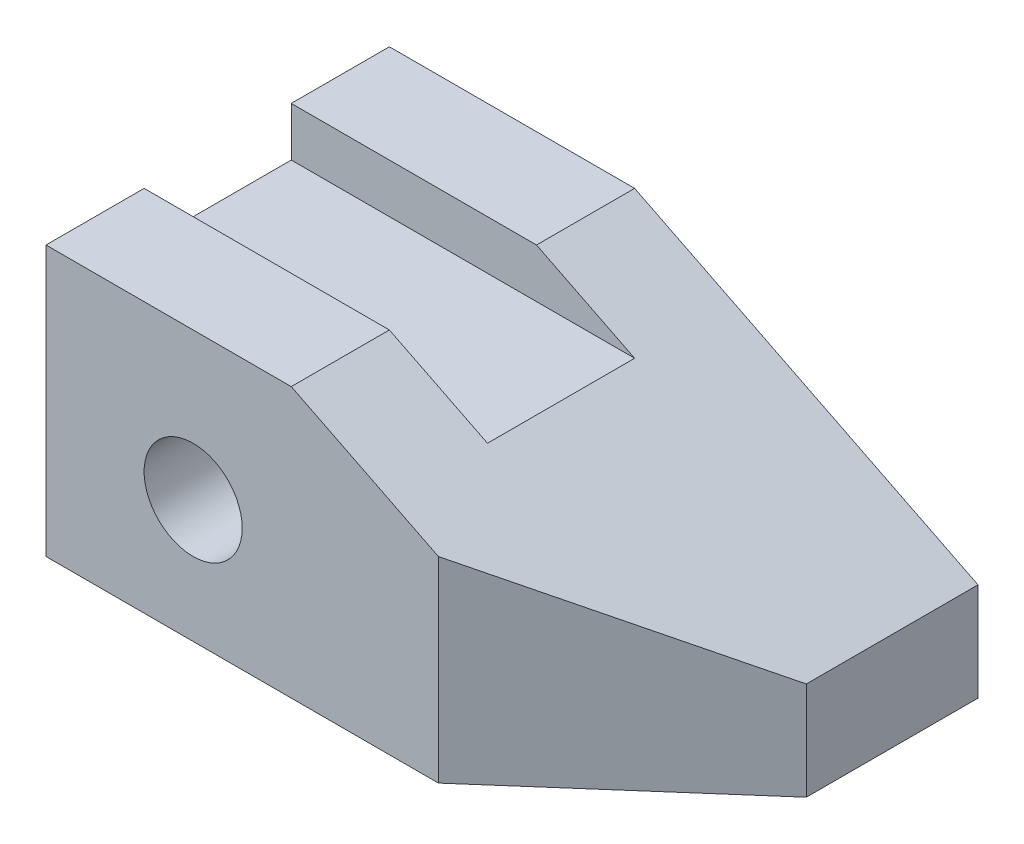
SolidWorks part; units mm, degrees
ref_plane "Front Plane" through (0, 0, 0) normal (0, 0, 1) x (1, 0, 0)
ref_plane "Top Plane" through (0, 0, 0) normal (0, 1, 0) x (1, 0, 0)
ref_plane "Right Plane" through (0, 0, 0) normal (1, 0, 0) x (0, 0, -1)
sketch "Sketch2" plane through (0, 0, 0) normal (0, 1, 0) x (1, 0, 0)
  line L1 (0, 0) -> (152.4, 0)
  line L2 (0, 0) -> (0, 88.9)
  line L3 (0, 88.9) -> (152.4, 88.9)
  line L4 (152.4, 0) -> (152.4, 88.9)
  dimension "D1" = 152.4
  dimension "D2" = 88.9
extrude "Boss-Extrude1" add sketch "Sketch2" along normal blind 69.85
sketch "Sketch3" plane through (0, 0, 0) normal (0, 0, 1) x (1, 0, 0)
  line L0 (63.5, 69.85) -> (152.4, 25.4)
  line L1 (0, 69.85) -> (152.4, 69.85) construction
  line L2 (152.4, 69.85) -> (152.4, 0) construction
  line L3 (0, 69.85) -> (0, 0) construction
  line L4 (0, 0) -> (152.4, 0) construction
  circle A0 centre (38.1, 31.75) radius 12.7
  line M2 (152.4, 0) -> (152.4, 69.85)
  line M3 (152.4, 69.85) -> (0, 69.85)
  dimension "D3" = 25.4
  dimension "D1" = 63.5
  dimension "D2" = 25.4
  dimension "D4" = 38.1
  dimension "D5" = 31.75
extrude "Cut-Extrude1" cut sketch "Sketch3" against normal through all contours L0 M3 M2 | A0
sketch "Sketch5" plane through (0, 69.85, 0) normal (0, 1, 0) x (1, 0, 0)
  line L0 (101.6, 0) -> (152.4, 44.45)
  line L1 (63.5, 88.9) -> (152.4, 88.9) construction
  line L2 (152.4, 88.9) -> (152.4, 0) construction
  line L3 (63.5, 0) -> (152.4, 0) construction
  line L4 (0, 88.9) -> (0, 0) construction
  line L6 (152.4, 0) -> (101.6, 0)
  line L7 (152.4, 0) -> (152.4, 44.45)
  dimension "D1" = 44.45
  dimension "D2" = 101.6
extrude "Cut-Extrude4" cut sketch "Sketch5" against normal through all
sketch "Sketch6" plane through (0, 0, 0) normal (-1, 0, 0) x (0, 0, 1)
  line L0 (-88.9, 69.85) -> (0, 69.85) construction
  line L1 (-63.5, 69.85) -> (-25.4, 69.85)
  line L2 (-63.5, 69.85) -> (-63.5, 57.15)
  line L3 (-63.5, 57.15) -> (-25.4, 57.15)
  line L4 (-25.4, 69.85) -> (-25.4, 57.15)
  line L5 (-88.9, 69.85) -> (-88.9, 0) construction
  dimension "D1" = 12.7
  dimension "D2" = 38.1
  dimension "D3" = 25.4
extrude "Cut-Extrude5" cut sketch "Sketch6" against normal through all
